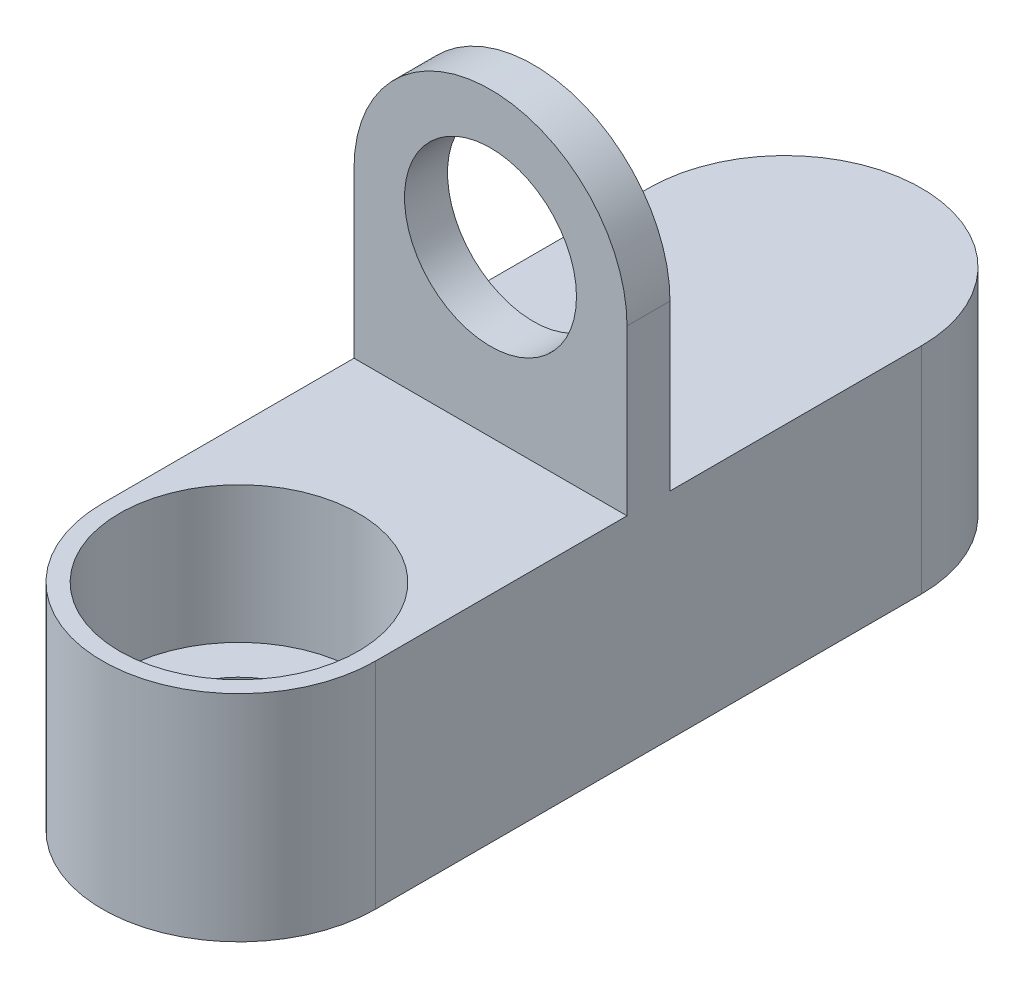
SolidWorks part; units mm, degrees
ref_plane "Front Plane" through (0, 0, 0) normal (0, 0, 1) x (1, 0, 0)
ref_plane "Top Plane" through (0, 0, 0) normal (0, 1, 0) x (1, 0, 0)
ref_plane "Right Plane" through (0, 0, 0) normal (1, 0, 0) x (0, 0, -1)
sketch "Sketch1" plane through (0, 0, 0) normal (0, 1, 0) x (1, 0, 0)
  line L0 (0, 12.7) -> (0, -12.7) construction
  line L1 (6.35, 12.7) -> (6.35, -12.7)
  line L2 (-6.35, 12.7) -> (-6.35, -12.7)
  arc A0 (6.35, 12.7) -> (-6.35, 12.7) centre (0, 12.7) ccw
  arc A1 (-6.35, -12.7) -> (6.35, -12.7) centre (0, -12.7) ccw
  point P2 (0, 0)
  dimension "D1" = 12.7
  dimension "D3" = 25.4
extrude "Boss-Extrude1" add sketch "Sketch1" along normal blind 10
hole_wizard "CBORE for 1/4 Socket Head Cap Screw1" positions "Sketch2" profile "Sketch4" counterbore size "1/4" standard "ANSI Inch" end condition through all
sketch "Sketch2" plane through (0, 10, 0) normal (0, 1, 0) x (1, 0, 0)
  point P0 (0, -12.7)
sketch "Sketch4" plane through (0, 10, 12.7) normal (1, 0, 0) x (0, 0, 1)
  line L0 (0, 0) -> (0, 10)
  line L1 (0, 10) -> (3.5712, 10)
  line L3 (3.5712, 10) -> (3.5712, 6.35)
  line L4 (3.5712, 6.35) -> (5.5562, 6.35)
  line L5 (5.5562, 6.35) -> (5.5562, 0)
  line L7 (5.5562, 0) -> (0, 0)
  line L11 (0, -6.35) -> (0, 107.95) construction
  dimension "Thru Hole Dia." = 7.1425
  dimension "Thru Hole Depth" = 10
  dimension "C'Bore Dia." = 11.1125
  dimension "C'Bore Depth" = 6.35
sketch "Sketch5" plane through (0, 10, 0) normal (0, 1, 0) x (1, 0, 0)
  line L0 (6.35, -12.7) -> (6.35, 12.7) construction
  line L1 (-6.35, 1) -> (6.35, 1)
  line L2 (-6.35, 1) -> (-6.35, -1)
  line L3 (-6.35, -1) -> (6.35, -1)
  line L4 (6.35, 1) -> (6.35, -1)
  line L5 (-6.35, 1) -> (6.35, -1) construction
  line L6 (-6.35, -1) -> (6.35, 1) construction
  point P0 (0, 0)
  dimension "D1" = 2
extrude "Boss-Extrude2" add sketch "Sketch5" along normal blind 14
sketch "Sketch6" plane through (0, 0, 1) normal (0, 0, 1) x (1, 0, 0)
  line L0 (-6.35, 24) -> (6.35, 24) construction
  line L1 (-6.35, 24) -> (-6.35, 10) construction
  line L2 (6.35, 24) -> (6.35, 10) construction
  line L3 (-6.35, 17.65) -> (-6.35, 24)
  line L4 (-6.35, 24) -> (6.35, 24)
  line L5 (6.35, 24) -> (6.35, 17.65)
  arc A0 (6.35, 17.65) -> (-6.35, 17.65) centre (0, 17.65) ccw
  line M3 (6.35, 10) -> (6.35, 24)
  line M4 (6.35, 24) -> (-6.35, 24)
  line M5 (-6.35, 24) -> (-6.35, 10)
extrude "Cut-Extrude1" cut sketch "Sketch6" against normal blind 10 contours A0 L4 M5 | A0 M3 M4
sketch "Sketch7" plane through (0, 0, 1) normal (0, 0, 1) x (1, 0, 0)
  circle A0 centre (0, 17.65) radius 4
  dimension "D1" = 8
extrude "Cut-Extrude2" cut sketch "Sketch7" against normal blind 10
